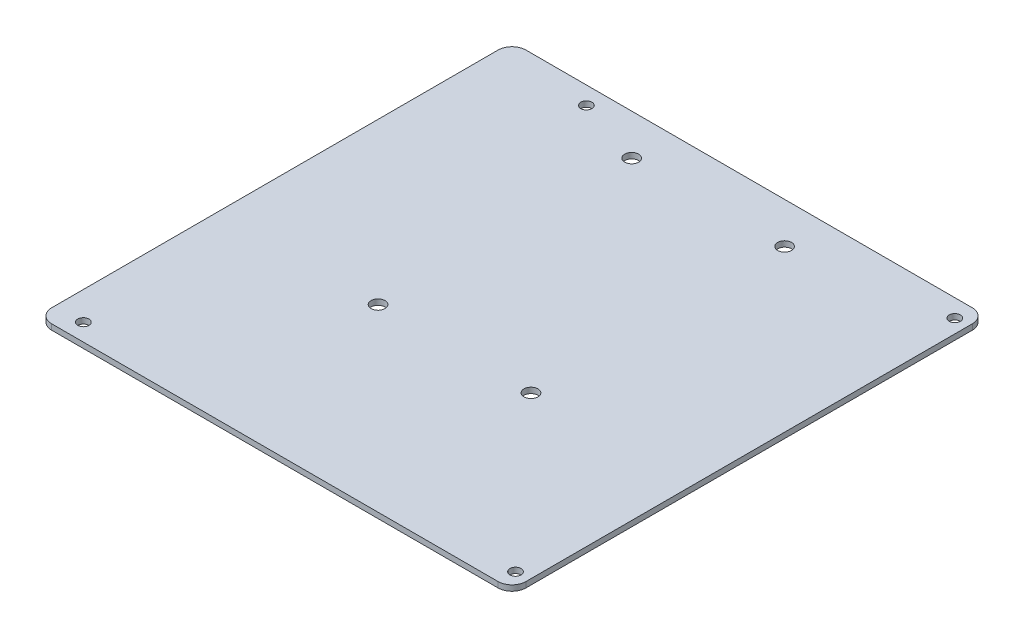
SolidWorks part; units mm, degrees
ref_plane "Спереди" through (0, 0, 0) normal (0, 0, 1) x (1, 0, 0)
ref_plane "Сверху" through (0, 0, 0) normal (0, 1, 0) x (1, 0, 0)
ref_plane "Справа" through (0, 0, 0) normal (1, 0, 0) x (0, 0, -1)
ref_plane "Плоскость4" through (0, 0, 0) normal (0, -1, 0) x (1, 0, 0)
sketch "Эскиз1" plane through (0, 0, 0) normal (0, -1, 0) x (1, 0, 0)
  line L0 (80, 85) -> (-80, 85)
  line L1 (-85, 80) -> (-85, -80)
  line L2 (-80, -85) -> (80, -85)
  line L3 (85, -80) -> (85, 80)
  line L4 (-84.5862, 0.9333) -> (85.4138, 0.9333) construction
  arc A0 (85, 80) -> (80, 85) centre (80, 80) ccw
  arc A1 (-80, 85) -> (-85, 80) centre (-80, 80) ccw
  arc A2 (-85, -80) -> (-80, -85) centre (-80, -80) ccw
  arc A3 (80, -85) -> (85, -80) centre (80, -80) ccw
  circle A10 centre (-74.84, 78.83) radius 2
  circle A11 centre (80.1, 78.83) radius 2
  circle A12 centre (80.1, -78.65) radius 2
  circle A13 centre (-51.98, -78.65) radius 2
extrude "Бобышка-Вытянуть1" add sketch "Эскиз1" against normal blind 2
sketch "Эскиз3" plane through (0, 2, 0) normal (0, 1, 0) x (1, 0, 0)
  circle A0 centre (-27.4895, -20.5339) radius 2.5
  circle A1 centre (-27.4895, 70.394) radius 2.5
  circle A2 centre (27.3345, -20.5339) radius 2.5
  circle A3 centre (27.3345, 70.394) radius 2.5
extrude "Вырез-Вытянуть1" cut sketch "Эскиз3" against normal blind 10
